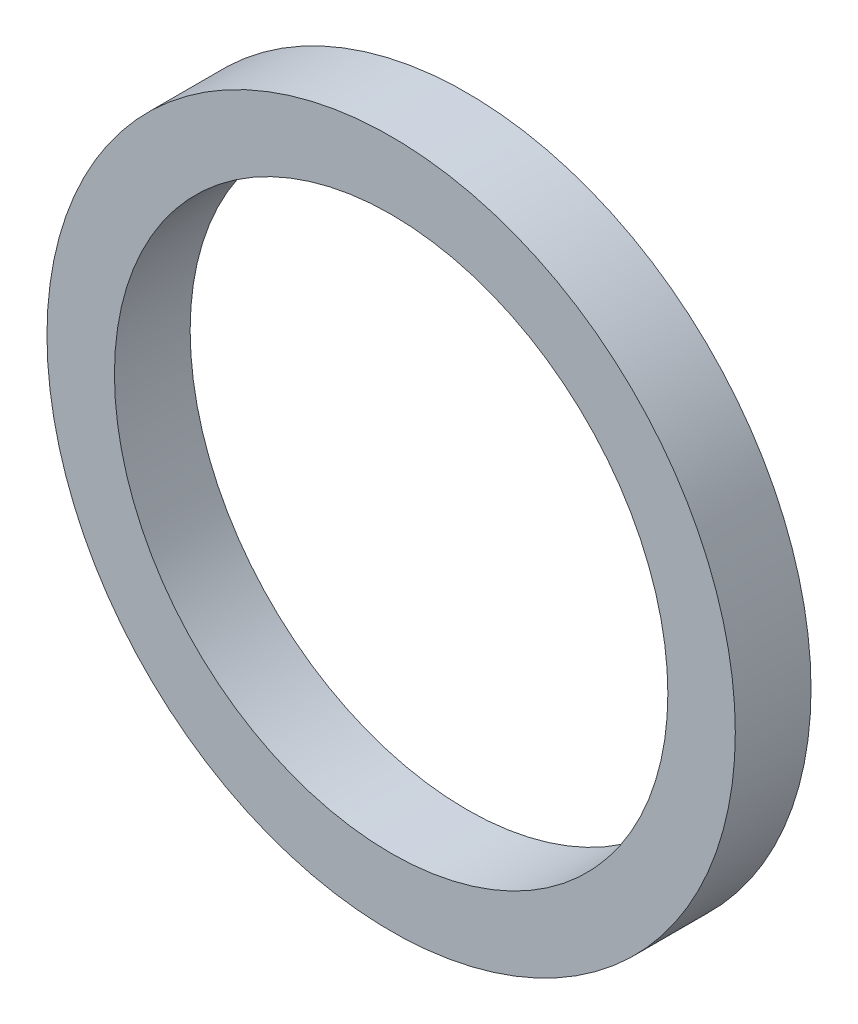
SolidWorks part; units mm, degrees
material "ABS"
ref_plane "前视基准面" through (0, 0, 0) normal (0, 0, 1) x (1, 0, 0)
ref_plane "上视基准面" through (0, 0, 0) normal (0, 1, 0) x (1, 0, 0)
ref_plane "右视基准面" through (0, 0, 0) normal (1, 0, 0) x (0, 0, -1)
sketch "草图1" plane through (0, 0, 0) normal (0, 0, 1) x (1, 0, 0)
  line L0 (-87.1056, 0) -> (87.1056, 0) construction
  line L1 (0, 87.1056) -> (0, -87.1056) construction
  circle A0 centre (0, 0) radius 20.1
  circle A1 centre (0, 0) radius 25
  dimension "D1" = 40.2
  dimension "D2" = 50
extrude "凸台-拉伸1" add sketch "草图1" along normal blind 5.5
